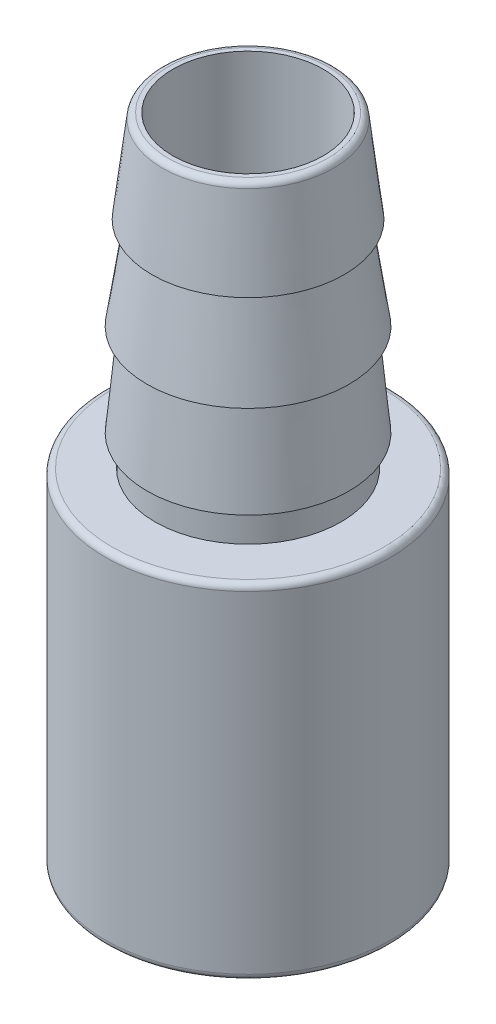
SolidWorks part; units mm, degrees
ref_plane "Front Plane" through (0, 0, 0) normal (0, 0, 1) x (1, 0, 0)
ref_plane "Top Plane" through (0, 0, 0) normal (0, 1, 0) x (1, 0, 0)
ref_plane "Right Plane" through (0, 0, 0) normal (1, 0, 0) x (0, 0, -1)
sketch "Sketch3" plane through (0, 0, 0) normal (0, 0, 1) x (1, 0, 0)
  line L0 (0, 70.3957) -> (0, 0) construction
  line L14 (0, 0) -> (27.0488, 0) construction
  line L38 (7.8, 45.3957) -> (7.1, 45.3957)
  line L41 (6.9, 52.8957) -> (7.8, 45.3957)
  line L44 (8.2, 37.8957) -> (7.5, 37.8957)
  line L47 (7.1, 45.3957) -> (8.2, 37.8957)
  line L56 (8.2, 37.8957) -> (8.2, 30.3957) construction
  line L57 (7.55, 30.3957) -> (8.2, 30.3957)
  line L58 (8.2, 30.3957) -> (7.5, 37.8957)
  line L59 (6.9, 52.8957) -> (6.1, 52.8957)
  line L63 (11.55, 27.8957) -> (7.55, 27.8957)
  line L64 (7.55, 27.8957) -> (7.55, 30.3957)
  line L65 (6.1, 25.8957) -> (6.1, 52.8957)
  line L69 (7.55, 25.8957) -> (7.55, 0)
  line L70 (11.55, 27.8957) -> (11.55, 0)
  line L71 (11.55, 0) -> (7.55, 0)
  line L72 (7.55, 25.8957) -> (6.1, 25.8957)
  dimension "D1" = 6.1
  dimension "D3" = 7.55
  dimension "D4" = 0.8
  dimension "D5" = 7.5
  dimension "D6" = 15.1
  dimension "D7" = 0
  dimension "D11" = 4
  dimension "D12" = 2.5
  dimension "D13" = 7.5
  dimension "D14" = 0.65
  dimension "D25" = 0.7
  dimension "D26" = 7.5
  dimension "D27" = 0.7
revolve "Revolve1" add sketch "Sketch3" angle 360 about L0
fillet "Redondeo2" radius 0.5 3 edges at (0, 0, 7.55) (0, 0, 11.55) (0, 27.8957, 11.55)
sketch "Croquis1" plane through (0, 0, 0) normal (0, 0, 1) x (1, 0, 0)
  circle A0 centre (0, 13.675) radius 1
  dimension "D1" = 2
extrude "Cortar-Extruir1" cut sketch "Croquis1" against normal through all
fillet "Redondeo4" radius 0.5 1 edges at (0, 52.8957, 6.9)
